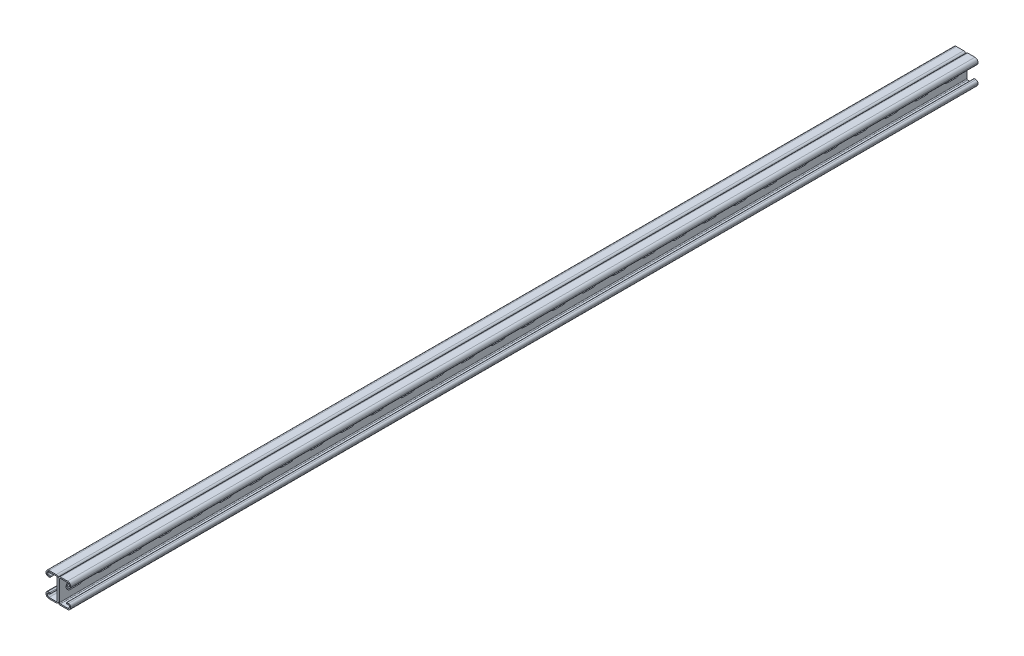
SolidWorks part; units mm, degrees
ref_plane "Front Plane" through (0, 0, 0) normal (0, 0, 1) x (1, 0, 0)
ref_plane "Top Plane" through (0, 0, 0) normal (0, 1, 0) x (1, 0, 0)
ref_plane "Right Plane" through (0, 0, 0) normal (1, 0, 0) x (0, 0, -1)
sketch "Sketch1" plane through (0, 0, 0) normal (0, 0, 1) x (1, 0, 0)
  line L0 (0, 0) -> (-20.6375, 0) construction
  line L3 (-20.6375, 20.6375) -> (0, 20.6375) construction
  line L4 (-20.6375, 20.6375) -> (-20.6375, -20.6375) construction
  line L5 (-20.6375, -20.6375) -> (0, -20.6375) construction
  line L6 (0, 20.6375) -> (0, -20.6375) construction
  line L7 (-15.5892, 20.6375) -> (-3.4607, 20.6375)
  line L8 (0, 17.1767) -> (0, -17.1767)
  line L9 (-2.032, -17.1767) -> (-2.032, 17.1767)
  line L10 (-3.4607, 18.6055) -> (-15.5892, 18.6055)
  line L11 (-20.6375, 15.5892) -> (-20.6375, 14.5732)
  line L12 (-17.1767, 11.1125) -> (-14.5161, 11.1125)
  line L14 (-14.5161, 13.1445) -> (-17.1767, 13.1445)
  line L15 (-18.6055, 14.5732) -> (-18.6055, 15.5892)
  line L16 (-18.6055, -14.5732) -> (-18.6055, -15.5892)
  line L17 (-14.5161, -13.1445) -> (-17.1767, -13.1445)
  line L18 (-17.1767, -11.1125) -> (-14.5161, -11.1125)
  line L19 (-20.6375, -15.5892) -> (-20.6375, -14.5732)
  line L20 (-3.4607, -18.6055) -> (-15.5892, -18.6055)
  line L21 (-15.5892, -20.6375) -> (-3.4607, -20.6375)
  line L22 (-2.032, -20.6375) -> (-2.032, 20.6375) construction
  arc A1 (0, 17.1767) -> (-3.4607, 20.6375) centre (-3.4607, 17.1767) ccw
  arc A2 (-2.032, 17.1767) -> (-3.4607, 18.6055) centre (-3.4607, 17.1767) ccw
  arc A4 (-15.5892, 20.6375) -> (-20.6375, 15.5892) centre (-15.5892, 15.5892) ccw
  arc A5 (-20.6375, 14.5732) -> (-17.1767, 11.1125) centre (-17.1767, 14.5732) ccw
  arc A6 (-14.5161, 11.1125) -> (-14.5161, 13.1445) centre (-14.5161, 12.1285) ccw
  arc A7 (-17.1767, 13.1445) -> (-18.6055, 14.5732) centre (-17.1767, 14.5732) cw
  arc A8 (-18.6055, 15.5892) -> (-15.5892, 18.6055) centre (-15.5892, 15.5892) cw
  arc A9 (-18.6055, -15.5892) -> (-15.5892, -18.6055) centre (-15.5892, -15.5892) ccw
  arc A10 (-17.1767, -13.1445) -> (-18.6055, -14.5732) centre (-17.1767, -14.5732) ccw
  arc A11 (-14.5161, -11.1125) -> (-14.5161, -13.1445) centre (-14.5161, -12.1285) cw
  arc A12 (-20.6375, -14.5732) -> (-17.1767, -11.1125) centre (-17.1767, -14.5732) cw
  arc A13 (-15.5892, -20.6375) -> (-20.6375, -15.5892) centre (-15.5892, -15.5892) cw
  arc A14 (-2.032, -17.1767) -> (-3.4607, -18.6055) centre (-3.4607, -17.1767) cw
  arc A15 (0, -17.1767) -> (-3.4607, -20.6375) centre (-3.4607, -17.1767) cw
  point P24 (0, 20.6375)
  point P65 (-2.032, 0)
  dimension "D1" = 3.4608
  dimension "D2" = 5.0482
  dimension "D3" = 3.4608
  dimension "Ht." = 20.6375
  dimension "Wd." = 41.275
  dimension "Thk." = 2.032
  dimension "D4" = 9.525
  dimension "D5" = 7.1374
extrude "Boss-Extrude1" add sketch "Sketch1" against normal blind 1524
sketch "Sketch3" plane through (0, 0, 0) normal (1, 0, 0) x (0, 0, -1)
  line L0 (0, 0) -> (1524, 0) construction
  point P2 (101.6, 0)
  point P3 (1422.4, 0)
  dimension "D1" = 101.6
  dimension "D2" = 101.6
  dimension "D3" = 1524
sketch "Sketch2" plane through (0, 0, 0) normal (1, 0, 0) x (0, 0, -1)
  line L0 (18.2562, 0) -> (32.5437, 0) construction
  line L1 (18.2562, 7.1437) -> (32.5437, 7.1437)
  line L2 (18.2562, -7.1437) -> (32.5437, -7.1437)
  line L3 (18.2562, 0) -> (0, 0) construction
  line L4 (25.4, 0) -> (76.2, 0) construction
  line L5 (0, -17.1767) -> (0, 17.1767) construction
  arc A0 (18.2562, 7.1437) -> (18.2562, -7.1437) centre (18.2562, 0) ccw
  arc A1 (32.5437, -7.1437) -> (32.5437, 7.1437) centre (32.5437, 0) ccw
  point P3 (25.4, 0)
  dimension "Slot Lg." = 28.575
  dimension "D2" = 25.4
  dimension "Slot Wd." = 14.2875
  dimension "Slot Ctr." = 50.8
  dimension "Hole to End" = 11.1125
extrude "Cut-Extrude1" cut sketch "Sketch2" against normal up to vertex (2.032 mm away) up to point (-2.032, 0, 0)
pattern_linear "LPattern1" count 30 spacing 50.8 along (0, 0, -1) of "Cut-Extrude1"
mirror "Mirror1" about plane through (0, 17.1767, -1524) normal (1, 0, 0) of bodies 116
equation "\"D1@LPattern1\" = \"Slot Ctr.@Sketch2\""
equation "\"Hole Count@LPattern1\" = \"Lg.@Boss-Extrude1\" / \"D1@LPattern1\""
equation "\"D3@Sketch3\" = \"Lg.@Boss-Extrude1\""
